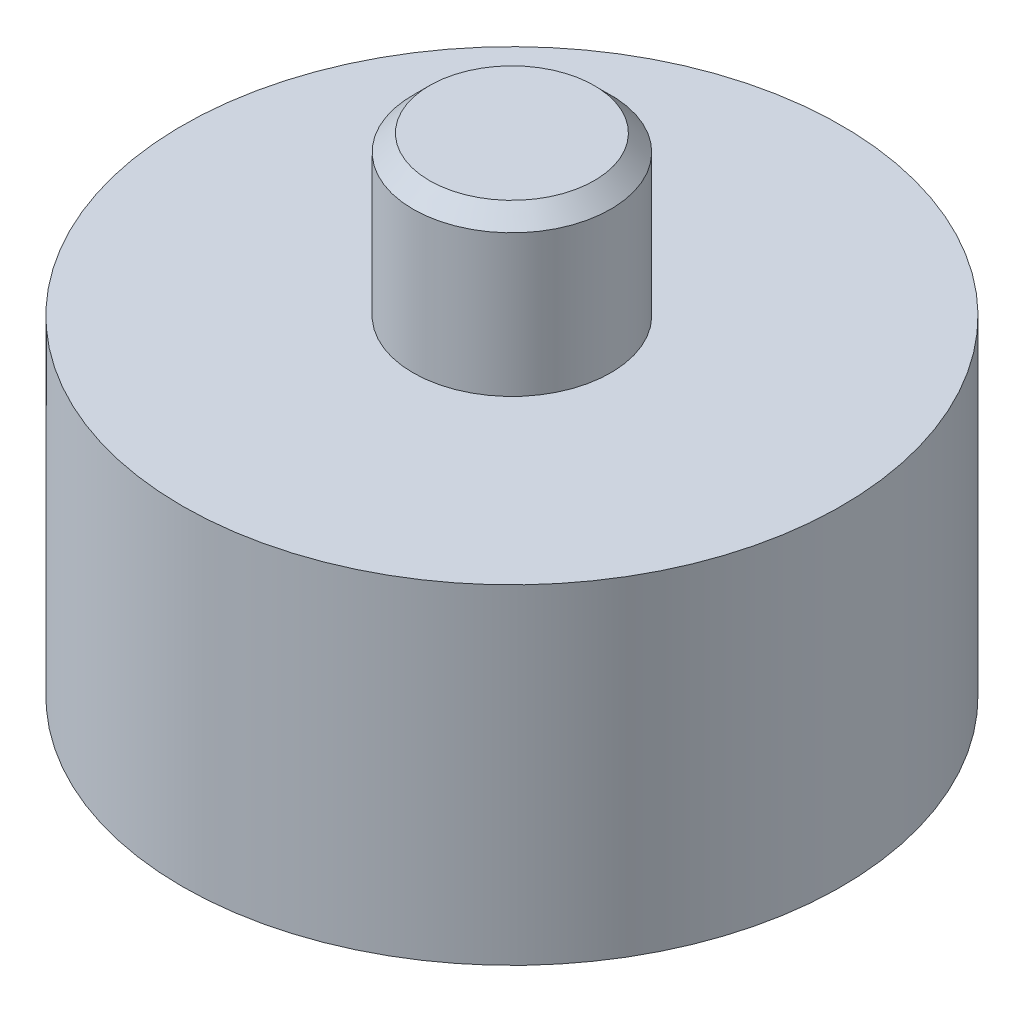
SolidWorks part; units mm, degrees
ref_plane "Piano frontale" through (0, 0, 0) normal (0, 0, 1) x (1, 0, 0)
ref_plane "Piano superiore" through (0, 0, 0) normal (0, 1, 0) x (1, 0, 0)
ref_plane "Piano destro" through (0, 0, 0) normal (1, 0, 0) x (0, 0, -1)
sketch "Schizzo1" plane through (0, 0, 0) normal (0, 1, 0) x (1, 0, 0)
  circle A0 centre (0, 0) radius 10
  dimension "D1" = 20
extrude "Estrusione-Estrusione1" add sketch "Schizzo1" along normal blind 10
sketch "Schizzo2" plane through (0, 0, 0) normal (0, -1, 0) x (1, 0, 0)
  circle A0 centre (0, 0) radius 3
  dimension "D1" = 6
extrude "Estrusione-Estrusione2" add sketch "Schizzo2" against normal offset from surface (19.6 mm away) 4.8 from offset 4.8
sketch "Schizzo3" plane through (0, 0, 0) normal (0, 0, 1) x (1, 0, 0)
  line L3 (-10, 0) -> (10, 0) construction
  circle A0 centre (0, 5) radius 3
  point P2 (0, 0)
  point P4 (0, 0)
  dimension "D1" = 6
  dimension "D2" = 5
extrude "Taglio-Estrusione1" cut sketch "Schizzo3" against normal blind 9.5 from offset 0.5 offset against normal yes
chamfer "Smusso1" distance 0.5 angle 45 2 edges at (0, -4.8, -3) (0, 14.8, 3)
